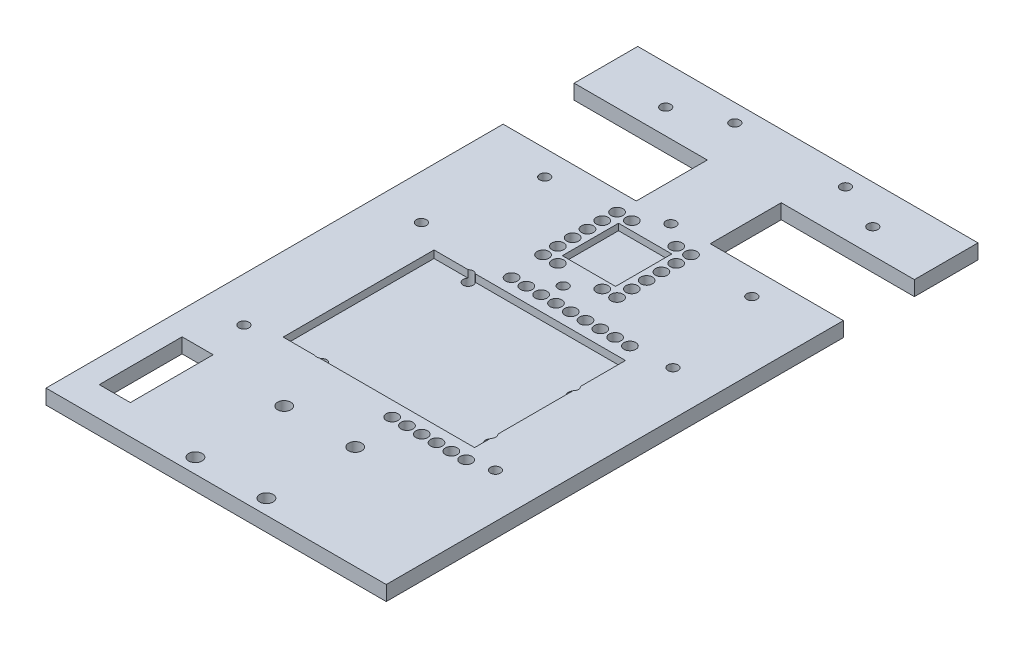
SolidWorks part; units mm, degrees
material "Náilon 6/10"
ref_plane "Plano frontal" through (0, 0, 0) normal (0, 0, 1) x (1, 0, 0)
ref_plane "Plano superior" through (0, 0, 0) normal (0, 1, 0) x (1, 0, 0)
ref_plane "Plano direito" through (0, 0, 0) normal (1, 0, 0) x (0, 0, -1)
sketch "Esboço1" plane through (0, 0, 0) normal (0, 1, 0) x (1, 0, 0)
  line L1 (0, 0) -> (115, 0)
  line L2 (0, 0) -> (0, 200)
  line L3 (0, 200) -> (115, 200)
  line L4 (115, 0) -> (115, 200)
  dimension "D1" = 115
  dimension "D2" = 200
extrude "Ressalto-extrusão1" add sketch "Esboço1" along normal blind 5
hole_wizard "Furo com folga de M41" positions "Esboço2" profile "Esboço4" hole size "M4" standard "Ansi Metric" end condition through all
sketch "Esboço2" plane through (0, 5, 0) normal (0, 1, 0) x (1, 0, 0)
  line L0 (0, 35) -> (45.5, 35) construction
  line L1 (0, 200) -> (0, 0) construction
  line L2 (45.5, 35) -> (69.5, 35) construction
  line L3 (69.5, 35) -> (115, 35) construction
  line L4 (115, 0) -> (115, 200) construction
  line L6 (0, 0) -> (115, 0) construction
  point P0 (45.5, 5)
  point P2 (69.5, 5)
  point P4 (69.5, 35)
  point P6 (45.5, 35)
  dimension "D1" = 24
  dimension "D2" = 30
  dimension "D3" = 5
sketch "Esboço4" plane through (45.5, 5, -5) normal (1, 0, 0) x (0, 0, 1)
  line L0 (0, 0) -> (0, 5)
  line L1 (0, 5) -> (2.25, 5)
  line L2 (2.25, 5) -> (2.25, 0)
  line L5 (2.25, 0) -> (0, 0)
  line L11 (0, -6.35) -> (0, 107.95) construction
  dimension "Thru Hole Dia." = 4.5
  dimension "Thru Hole Depth" = 5
sketch "Esboço5" plane through (0, 0, 0) normal (-1, 0, 0) x (0, 0, 1)
  line L0 (-200, 5) -> (0, 5) construction
  line L1 (-178.5, 5) -> (-154.5, 5)
  line L2 (-178.5, 5) -> (-178.5, 0)
  line L3 (-178.5, 0) -> (-154.5, 0)
  line L4 (-154.5, 5) -> (-154.5, 0)
  line L5 (-200, 0) -> (0, 0) construction
  line L6 (-200, 5) -> (-200, 0) construction
  dimension "D1" = 21.5
  dimension "D2" = 24
extrude "Corte-extrusão1" cut sketch "Esboço5" against normal blind 45
sketch "Esboço6" plane through (115, 0, 0) normal (1, 0, 0) x (0, 0, -1)
  line L0 (0, 0) -> (200, 0) construction
  line L1 (154.5, 0) -> (178.5, 0)
  line L2 (154.5, 0) -> (154.5, 5)
  line L3 (154.5, 5) -> (178.5, 5)
  line L4 (178.5, 0) -> (178.5, 5)
  line L5 (154.5, 0) -> (154.5, 5) construction
extrude "Corte-extrusão2" cut sketch "Esboço6" against normal blind 45
sketch "Esboço7" plane through (0, 5, 0) normal (0, 1, 0) x (1, 0, 0)
  line L0 (0, 80.5) -> (25.15, 80.5) construction
  line L1 (25.15, 55) -> (89.85, 55)
  line L2 (25.15, 55) -> (25.15, 106)
  line L3 (25.15, 106) -> (89.85, 106)
  line L4 (89.85, 55) -> (89.85, 106)
  line L5 (0, 154.5) -> (0, 0) construction
  line L6 (89.85, 80.5) -> (115, 80.5) construction
  line L7 (115, 0) -> (115, 154.5) construction
  line L8 (0, 0) -> (115, 0) construction
  dimension "D1" = 64.7
  dimension "D2" = 51
  dimension "D3" = 55
extrude "Corte-extrusão3" cut sketch "Esboço7" against normal blind 2.5
hole_wizard "Furo com folga de M31" positions "Esboço8" profile "Esboço9" hole size "M3" standard "Ansi Metric" end condition through all
sketch "Esboço8" plane through (0, 5, 0) normal (0, 1, 0) x (1, 0, 0)
  line L7 (25.15, 55) -> (89.85, 55) construction
  line L8 (36.62, 56.54) -> (88.69, 61.62) construction
  line L9 (88.69, 61.62) -> (88.69, 89.56) construction
  line L10 (88.69, 89.56) -> (37.89, 104.8) construction
  line L11 (37.89, 104.8) -> (36.62, 56.54) construction
  line L13 (89.85, 55) -> (89.85, 106) construction
  line L14 (25.15, 55) -> (89.85, 55) construction
  line L15 (89.85, 55) -> (89.85, 106) construction
  point P29 (88.69, 61.62)
  point P30 (88.69, 89.56)
  point P31 (37.89, 104.8)
  point P32 (36.62, 56.54)
  dimension "D1" = 1.54
  dimension "D2" = 1.16
  dimension "D3" = 6.62
  dimension "D4" = 34.56
  dimension "D5" = 53.23
  dimension "D6" = 51.96
  dimension "D8" = 49.8
sketch "Esboço9" plane through (88.69, 5, -61.62) normal (1, 0, 0) x (0, 0, 1)
  line L0 (0, 0) -> (0, 5)
  line L1 (0, 5) -> (1.7, 5)
  line L2 (1.7, 5) -> (1.7, 0)
  line L5 (1.7, 0) -> (0, 0)
  line L11 (0, -6.35) -> (0, 107.95) construction
  dimension "Thru Hole Dia." = 3.4
  dimension "Thru Hole Depth" = 5
sketch "Esboço10" plane through (0, 5, 0) normal (0, 1, 0) x (1, 0, 0)
  line L1 (48.5, 126) -> (66.5, 126)
  line L2 (48.5, 126) -> (48.5, 145)
  line L3 (48.5, 145) -> (66.5, 145)
  line L4 (66.5, 126) -> (66.5, 145)
  line L5 (0, 135.5) -> (48.5, 135.5) construction
  line L6 (0, 154.5) -> (0, 0) construction
  line L7 (66.5, 135.5) -> (115, 135.5) construction
  line L8 (115, 0) -> (115, 154.5) construction
  line L9 (115, 200) -> (0, 200) construction
  dimension "D1" = 18
  dimension "D2" = 19
  dimension "D3" = 55
extrude "Corte-extrusão4" cut sketch "Esboço10" against normal blind 2.2
sketch "Esboço11" plane through (0, 5, 0) normal (0, 1, 0) x (1, 0, 0)
  line L0 (0, 154.5) -> (0, 0) construction
  line L1 (8, 10) -> (18.5, 10)
  line L2 (8, 10) -> (8, 38)
  line L3 (8, 38) -> (18.5, 38)
  line L4 (18.5, 10) -> (18.5, 38)
  line L5 (0, 0) -> (115, 0) construction
  dimension "D1" = 28
  dimension "D2" = 10.5
  dimension "D3" = 8
  dimension "D4" = 10
extrude "Corte-extrusão5" cut sketch "Esboço11" against normal through all
hole_wizard "Furo com folga de M32" positions "Esboço14" profile "Esboço15" hole size "M3" standard "Ansi Metric" end condition through all
sketch "Esboço14" plane through (0, 0, 0) normal (0, -1, 0) x (-1, 0, 0)
  line L14 (0, 0) -> (-115, 0) construction
  line L15 (-115, 0) -> (-115, 154.5) construction
  point P20 (-15, 51.9)
  point P22 (-100, 51.9)
  point P24 (-100, 111.9)
  point P26 (-15, 111.9)
  dimension "D1" = 51.9
  dimension "D2" = 85
  dimension "D3" = 60
  dimension "D4" = 15
sketch "Esboço15" plane through (15, 0, -51.9) normal (1, 0, 0) x (0, 0, -1)
  line L0 (0, 0) -> (0, 5)
  line L1 (0, 5) -> (1.7, 5)
  line L2 (1.7, 5) -> (1.7, 0)
  line L5 (1.7, 0) -> (0, 0)
  line L11 (0, -6.35) -> (0, 107.95) construction
  dimension "Thru Hole Dia." = 3.4
  dimension "Thru Hole Depth" = 5
hole_wizard "Furo com folga de M33" positions "Esboço18" profile "Esboço19" hole size "M3" standard "Ansi Metric" end condition through all
sketch "Esboço18" plane through (0, 5, 0) normal (0, 1, 0) x (1, 0, 0)
  line L0 (57.5, 153.7) -> (57.5, 145) construction
  line L1 (66.5, 145) -> (48.5, 145) construction
  line L3 (48.5, 126) -> (66.5, 126) construction
  line L4 (57.5, 126) -> (57.5, 117.3) construction
  point P0 (57.5, 153.7)
  point P2 (57.5, 117.3)
  dimension "D1" = 36.4
sketch "Esboço19" plane through (57.5, 5, -153.7) normal (1, 0, 0) x (0, 0, 1)
  line L0 (0, 0) -> (0, 5)
  line L1 (0, 5) -> (1.7, 5)
  line L2 (1.7, 5) -> (1.7, 0)
  line L5 (1.7, 0) -> (0, 0)
  line L11 (0, -6.35) -> (0, 107.95) construction
  dimension "Thru Hole Dia." = 3.4
  dimension "Thru Hole Depth" = 5
hole_wizard "Furo com folga de M34" positions "Esboço20" profile "Esboço21" hole size "M3" standard "Ansi Metric" end condition through all
sketch "Esboço20" plane through (0, 5, 0) normal (0, 1, 0) x (1, 0, 0)
  line L0 (22.5, 186.95) -> (22.5, 178.5) construction
  line L1 (45, 178.5) -> (0, 178.5) construction
  line L3 (45, 154.5) -> (0, 154.5) construction
  line L4 (22.5, 154.5) -> (22.5, 146.05) construction
  line L5 (92.5, 186.95) -> (92.5, 178.5) construction
  line L6 (70, 178.5) -> (115, 178.5) construction
  line L8 (70, 154.5) -> (115, 154.5) construction
  line L9 (92.5, 154.5) -> (92.5, 146.05) construction
  point P0 (22.5, 186.95)
  point P2 (22.5, 146.05)
  point P17 (92.5, 186.95)
  point P19 (92.5, 146.05)
  dimension "D1" = 40.9
sketch "Esboço21" plane through (22.5, 5, -186.95) normal (1, 0, 0) x (0, 0, 1)
  line L0 (0, 0) -> (0, 5)
  line L1 (0, 5) -> (1.7, 5)
  line L2 (1.7, 5) -> (1.7, 0)
  line L5 (1.7, 0) -> (0, 0)
  line L11 (0, -6.35) -> (0, 107.95) construction
  dimension "Thru Hole Dia." = 3.4
  dimension "Thru Hole Depth" = 5
hole_wizard "Furo com folga de M35" positions "Esboço22" profile "Esboço23" hole size "M3" standard "Ansi Metric"
sketch "Esboço22" plane through (0, 5, 0) normal (0, 1, 0) x (1, 0, 0)
  line L0 (115, 200) -> (0, 200) construction
  line L2 (38.8, 194) -> (0, 194) construction
  line L3 (0, 200) -> (0, 178.5) construction
  line L5 (76.2, 194) -> (115, 194) construction
  line L6 (115, 178.5) -> (115, 200) construction
  point P0 (76.2, 194)
  point P2 (38.8, 194)
  dimension "D1" = 6
  dimension "D2" = 37.4
sketch "Esboço23" plane through (76.2, 5, -194) normal (1, 0, 0) x (0, 0, 1)
  line L0 (0, 0) -> (0, 12.2715)
  line L1 (0, 12.2715) -> (1.7, 11.25)
  line L2 (1.7, 11.25) -> (1.7, 0)
  line L5 (1.7, 0) -> (0, 0)
  line L10 (0, 12.2715) -> (-1.7, 11.25) construction
  line L11 (0, -6.35) -> (0, 107.95) construction
  dimension "Hole Dia." = 3.4
  dimension "Hole Depth" = 11.25
  dimension "Drill Angle" = 118
sketch "Esboço24" plane through (0, 5, 0) normal (0, 1, 0) x (1, 0, 0)
  line L0 (45, 148) -> (50, 148) construction
  line L1 (48.5, 145) -> (48.5, 126) construction
  line L2 (65, 148) -> (70, 148) construction
  line L3 (-951.5, 135.5) -> (49048.5, 135.5) construction
  line L4 (66.5, 126) -> (66.5, 145) construction
  line L5 (66.5, 145) -> (48.5, 145) construction
  line L6 (48.5, 145) -> (48.5, 126) construction
  line L7 (57.5, -855) -> (57.5, 49145) construction
  line L8 (70, 148) -> (70, 143) construction
  line L9 (70, 143) -> (70, 138) construction
  line L10 (70, 138) -> (70, 133) construction
  line L11 (70, 133) -> (70, 128) construction
  line L12 (70, 128) -> (70, 123) construction
  circle A0 centre (45, 148) radius 2
  circle A1 centre (50, 148) radius 2
  circle A2 centre (65, 148) radius 2
  circle A3 centre (70, 148) radius 2
  circle A4 centre (57.5, 135.5) radius 9 construction
  circle A5 centre (70, 143) radius 2
  circle A6 centre (70, 138) radius 2
  circle A7 centre (70, 133) radius 2
  circle A8 centre (70, 128) radius 2
  circle A9 centre (57.5, 135.5) radius 9 construction
  circle A10 centre (70, 123) radius 2
  circle A11 centre (65, 123) radius 2
  circle A12 centre (50, 123) radius 2
  circle A13 centre (45, 123) radius 2
  circle A14 centre (57.5, 135.5) radius 9 construction
  circle A15 centre (45, 128) radius 2
  circle A16 centre (45, 133) radius 2
  circle A17 centre (45, 138) radius 2
  circle A18 centre (45, 143) radius 2
  circle A19 centre (57.5, 135.5) radius 9 construction
  point P19 (48.5, 135.5)
  point P22 (57.5, 145)
  point P52 (57.5, 135.5)
  dimension "D1" = 4
  dimension "D2" = 3.5
  dimension "D3" = 3.5
  dimension "D4" = 3
  dimension "D5" = 18
  dimension "D6" = 5
  dimension "D7" = 5
  dimension "D8" = 3
  dimension "D9" = 25
extrude "Corte-extrusão6" cut sketch "Esboço24" against normal through all
sketch "Esboço26" plane through (0, 5, 0) normal (0, 1, 0) x (1, 0, 0)
  line L0 (39.0942, 106) -> (89.85, 106) construction
  line L1 (115, 0) -> (115, 154.5) construction
  circle A0 centre (66.35, 111) radius 2
  circle A1 centre (71.35, 111) radius 2
  circle A2 centre (76.35, 111) radius 2
  circle A3 centre (81.35, 111) radius 2
  circle A4 centre (86.35, 111) radius 2
  circle A5 centre (66.35, 111) radius 2
  circle A6 centre (71.35, 111) radius 2
  circle A7 centre (76.35, 111) radius 2
  circle A8 centre (81.35, 111) radius 2
  circle A9 centre (61.35, 111) radius 2
  circle A10 centre (66.35, 111) radius 2
  circle A11 centre (71.35, 111) radius 2
  circle A12 centre (76.35, 111) radius 2
  circle A13 centre (56.35, 111) radius 2
  circle A14 centre (61.35, 111) radius 2
  circle A15 centre (66.35, 111) radius 2
  circle A16 centre (71.35, 111) radius 2
  circle A17 centre (51.35, 111) radius 2
  circle A18 centre (56.35, 111) radius 2
  circle A19 centre (61.35, 111) radius 2
  circle A20 centre (66.35, 111) radius 2
  circle A21 centre (61.35, 111) radius 2
  circle A22 centre (56.35, 111) radius 2
  circle A23 centre (51.35, 111) radius 2
  circle A24 centre (46.35, 111) radius 2
  dimension "D1" = 4
  dimension "D2" = 5
  dimension "D3" = 48.65
  dimension "D4" = 5
  dimension "D5" = 5
extrude "Corte-extrusão7" cut sketch "Esboço26" against normal through all contours A24 | A17 | A9 | A0 | A1 | A3 | A4 | A13 | A2
sketch "Esboço27" plane through (0, 5, 0) normal (0, 1, 0) x (1, 0, 0)
  line L0 (37.34, 55) -> (89.85, 55) construction
  line L1 (115, 0) -> (115, 154.5) construction
  circle A0 centre (82, 50) radius 2
  circle A1 centre (87, 50) radius 2
  circle A2 centre (92, 50) radius 2
  circle A3 centre (82, 50) radius 2
  circle A4 centre (87, 50) radius 2
  circle A5 centre (77, 50) radius 2
  circle A6 centre (82, 50) radius 2
  circle A7 centre (72, 50) radius 2
  circle A8 centre (77, 50) radius 2
  circle A9 centre (77, 50) radius 2
  circle A10 centre (72, 50) radius 2
  circle A11 centre (67, 50) radius 2
  dimension "D1" = 4
  dimension "D2" = 5
  dimension "D3" = 33
  dimension "D4" = 3
  dimension "D5" = 4
extrude "Corte-extrusão8" cut sketch "Esboço27" against normal through all contours A2 | A0 | A11 | A5 | A7 | A1
